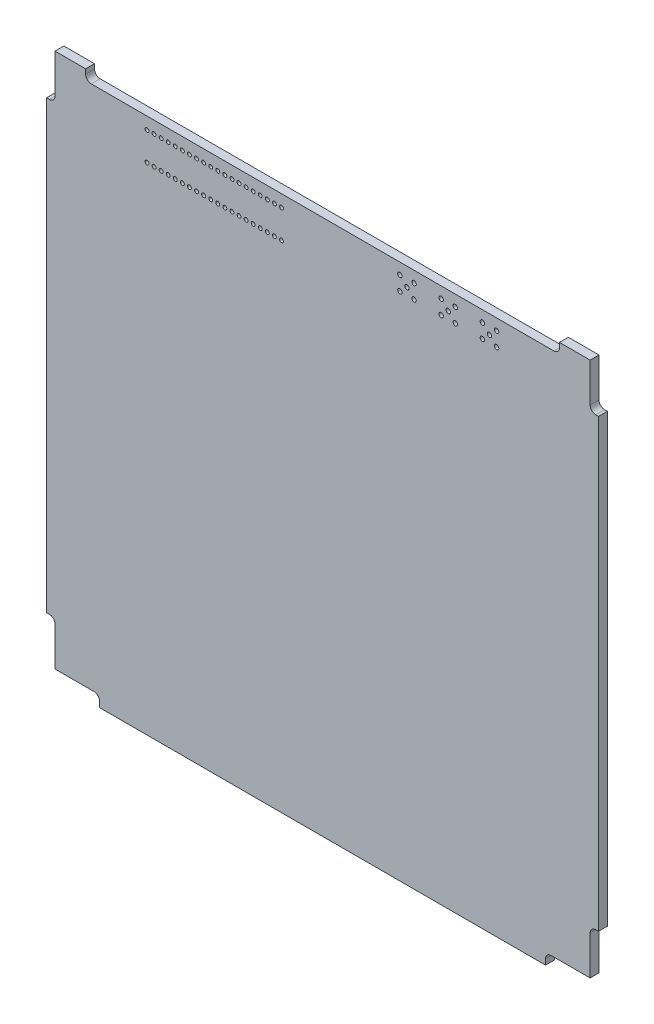
SolidWorks part; units mm, degrees
material "ABS"
ref_plane "Front Plane" through (0, 0, 0) normal (0, 0, 1) x (1, 0, 0)
ref_plane "Top Plane" through (0, 0, 0) normal (0, 1, 0) x (1, 0, 0)
ref_plane "Right Plane" through (0, 0, 0) normal (1, 0, 0) x (0, 0, -1)
sketch "Sketch1" plane through (0, 0, 0) normal (0, 0, 1) x (1, 0, 0)
  line L0 (-40, 50) -> (-40, 48)
  line L1 (-50, -50) -> (50, -50)
  line L2 (-50, -50) -> (-50, 50)
  line L3 (-50, 50) -> (50, 50)
  line L4 (50, -50) -> (50, 50)
  line L5 (-50, -50) -> (50, 50) construction
  line L6 (-50, 50) -> (50, -50) construction
  line L7 (-50, 50) -> (-40, 50)
  line L8 (-50, 50) -> (-50, 40)
  line L9 (-40, 48) -> (-48, 48)
  line L10 (-48, 48) -> (-48, 40)
  line L11 (50, 50) -> (40, 50)
  line L12 (50, 50) -> (50, 40)
  line L13 (-48, 40) -> (-50, 40)
  line L14 (50, 40) -> (48, 40)
  line L15 (-50, -50) -> (-37.8649, -50)
  line L16 (-50, -50) -> (-50, -37.8649)
  line L17 (50, 50) -> (50, 40)
  line L18 (50, 50) -> (40, 50)
  line L19 (50, -50) -> (41.5, -50)
  line L20 (50, -50) -> (50, -41.5)
  line L21 (48, 40) -> (48, 48)
  line L22 (48, 48) -> (40, 48)
  line L23 (40, 48) -> (40, 50)
  line L24 (40, -50) -> (40, -48)
  line L25 (50, -50) -> (40, -50)
  line L26 (50, -50) -> (50, -40)
  line L27 (40, -48) -> (48, -48)
  line L28 (48, -48) -> (48, -40)
  line L29 (48, -40) -> (50, -40)
  line L30 (-50, -40) -> (-48, -40)
  line L31 (-50, -50) -> (-50, -40)
  line L32 (-50, -50) -> (-40, -50)
  line L33 (-48, -40) -> (-48, -48)
  line L34 (-48, -48) -> (-40, -48)
  line L35 (-40, -48) -> (-40, -50)
  point P0 (0, 0)
  point P38 (0, 0)
  dimension "D1" = 100
  dimension "D2" = 100
  dimension "D3" = 2
  dimension "D4" = 10
  dimension "D5" = 4
extrude "Boss-Extrude1" add sketch "Sketch1" along normal blind 1.5875
sketch "Sketch2" plane through (0, 0, 1.5875) normal (0, 0, 1) x (1, 0, 0)
  line L0 (0, 50) -> (0, -50) construction
  line L1 (-40, 50) -> (40, 50) construction
  line L2 (-40, -50) -> (40, -50) construction
  line L3 (-50, -40) -> (-50, 40) construction
  line L4 (-40, 50) -> (40, 50) construction
  circle A0 centre (-31.5, 44) radius 0.35
  circle A1 centre (-30.23, 44) radius 0.35
  circle A2 centre (-28.96, 44) radius 0.35
  circle A3 centre (-27.69, 44) radius 0.35
  circle A4 centre (-26.42, 44) radius 0.35
  circle A5 centre (-25.15, 44) radius 0.35
  circle A6 centre (-23.88, 44) radius 0.35
  circle A7 centre (-22.61, 44) radius 0.35
  circle A8 centre (-21.34, 44) radius 0.35
  circle A9 centre (-20.07, 44) radius 0.35
  circle A10 centre (-18.8, 44) radius 0.35
  circle A11 centre (-17.53, 44) radius 0.35
  circle A12 centre (-16.26, 44) radius 0.35
  circle A13 centre (-14.99, 44) radius 0.35
  circle A14 centre (-13.72, 44) radius 0.35
  circle A15 centre (-12.45, 44) radius 0.35
  circle A16 centre (-11.18, 44) radius 0.35
  circle A17 centre (-9.91, 44) radius 0.35
  circle A18 centre (-8.64, 44) radius 0.35
  circle A19 centre (-7.37, 44) radius 0.35
  circle A20 centre (-30.23, 38.92) radius 0.35
  circle A21 centre (-28.96, 38.92) radius 0.35
  circle A22 centre (-27.69, 38.92) radius 0.35
  circle A23 centre (-26.42, 38.92) radius 0.35
  circle A24 centre (-25.15, 38.92) radius 0.35
  circle A25 centre (-23.88, 38.92) radius 0.35
  circle A26 centre (-22.61, 38.92) radius 0.35
  circle A27 centre (-21.34, 38.92) radius 0.35
  circle A28 centre (-20.07, 38.92) radius 0.35
  circle A29 centre (-18.8, 38.92) radius 0.35
  circle A30 centre (-17.53, 38.92) radius 0.35
  circle A31 centre (-16.26, 38.92) radius 0.35
  circle A32 centre (-14.99, 38.92) radius 0.35
  circle A33 centre (-13.72, 38.92) radius 0.35
  circle A34 centre (-12.45, 38.92) radius 0.35
  circle A35 centre (-11.18, 38.92) radius 0.35
  circle A36 centre (-9.91, 38.92) radius 0.35
  circle A37 centre (-8.64, 38.92) radius 0.35
  circle A38 centre (-7.37, 38.92) radius 0.35
  circle A39 centre (-31.5, 38.92) radius 0.35
  dimension "D1" = 0.7
  dimension "D4" = 18.5
  dimension "D5" = 6
  dimension "D2" = 5.08
  dimension "D3" = 1.27
extrude "Cut-Extrude1" cut sketch "Sketch2" against normal through all
sketch "Sketch3" plane through (0, 50, 0) normal (0, 1, 0) x (1, 0, 0)
  line L0 (-40, 0) -> (40, 0) construction
  line L1 (10.7, 0) -> (19.7, 0)
  line L2 (10.7, 0) -> (10.7, -1.5875)
  line L3 (10.7, -1.5875) -> (19.7, -1.5875)
  line L4 (-40, -1.5875) -> (-40, 0) construction
  line L5 (-40, -1.5875) -> (40, -1.5875) construction
  line L6 (15.2, 0) -> (15.2, -1.5875) construction
  line L7 (12, 0) -> (12, -1.5875) construction
  line L8 (18.4, 0) -> (18.4, -1.5875) construction
  line L9 (-40, -1.5875) -> (40, -1.5875) construction
  line L12 (19.7, 0) -> (34.5, 0)
  line L14 (19.7, -1.5875) -> (34.5, -1.5875)
  line L15 (34.5, 0) -> (34.5, -1.5875)
  dimension "D1" = 9
  dimension "D2" = 6.4
  dimension "D3" = 3.2
  dimension "D5" = 14.8
  dimension "D6" = 50.7
extrude "Cut-Extrude2" cut sketch "Sketch3" against normal blind 3.8375
fillet "Fillet2" radius 1 2 edges at (10.7, 46.1625, 0.7938) (34.5, 46.1625, 0.7937)
sketch "Sketch5" plane through (0, 0, 0) normal (0, 0, -1) x (-1, 0, 0)
  line L0 (40, -50) -> (-40, -50) construction
  line L1 (-49.5, 50) -> (49.5, 50)
  line L2 (-49.5, 50) -> (-49.5, -50)
  line L3 (-49.5, -50) -> (49.5, -50)
  line L4 (49.5, 50) -> (49.5, -50)
  line L5 (40, 50) -> (-10.7, 50) construction
  line L6 (50, -40) -> (50, 40) construction
  dimension "D1" = 99
  dimension "D2" = 0.5
extrude "Cut-Extrude3" cut sketch "Sketch5" against normal through all flip side to cut
sketch "Sketch6" plane through (0, 0, 1.5875) normal (0, 0, 1) x (1, 0, 0)
  line L0 (11.7, 46.1625) -> (33.5, 46.1625) construction
  line L1 (28.67, 41.6225) -> (31.21, 41.6225) construction
  line L2 (28.67, 41.6225) -> (28.67, 44.1625) construction
  line L3 (28.67, 44.1625) -> (31.21, 44.1625) construction
  line L4 (31.21, 41.6225) -> (31.21, 44.1625) construction
  line L5 (28.67, 41.6225) -> (31.21, 44.1625) construction
  line L6 (28.67, 44.1625) -> (31.21, 41.6225) construction
  line L7 (34.5, 47.1625) -> (34.5, 50) construction
  line L8 (21.27, 41.6225) -> (23.81, 41.6225) construction
  line L9 (21.27, 41.6225) -> (21.27, 44.1625) construction
  line L10 (21.27, 44.1625) -> (23.81, 44.1625) construction
  line L11 (23.81, 41.6225) -> (23.81, 44.1625) construction
  line L12 (21.27, 41.6225) -> (23.81, 44.1625) construction
  line L13 (21.27, 44.1625) -> (23.81, 41.6225) construction
  line L14 (13.87, 41.6225) -> (16.41, 41.6225) construction
  line L17 (13.87, 41.6225) -> (13.87, 44.1625) construction
  line L18 (13.87, 44.1625) -> (16.41, 44.1625) construction
  line L19 (16.41, 41.6225) -> (16.41, 44.1625) construction
  line L20 (13.87, 41.6225) -> (16.41, 44.1625) construction
  line L21 (13.87, 44.1625) -> (16.41, 41.6225) construction
  circle A0 centre (29.94, 42.8925) radius 0.4
  circle A1 centre (28.67, 44.1625) radius 0.4
  circle A2 centre (31.21, 44.1625) radius 0.4
  circle A3 centre (31.21, 41.6225) radius 0.4
  circle A4 centre (28.67, 41.6225) radius 0.4
  circle A5 centre (22.54, 42.8925) radius 0.4
  circle A6 centre (21.27, 44.1625) radius 0.4
  circle A7 centre (23.81, 44.1625) radius 0.4
  circle A8 centre (23.81, 41.6225) radius 0.4
  circle A9 centre (21.27, 41.6225) radius 0.4
  circle A10 centre (15.14, 42.8925) radius 0.4
  circle A11 centre (13.87, 44.1625) radius 0.4
  circle A12 centre (16.41, 44.1625) radius 0.4
  circle A13 centre (16.41, 41.6225) radius 0.4
  circle A14 centre (13.87, 41.6225) radius 0.4
  point P23 (27.2, 39.7784)
  point P32 (19.8, 39.7784)
  dimension "D1" = 2.54
  dimension "D2" = 0.8
  dimension "D3" = 2.54
  dimension "D4" = 3.27
  dimension "D5" = 4.56
  dimension "D6" = 7.4
  dimension "D8" = 2
  dimension "D7" = 3
sketch "Sketch7" plane through (0, 0, 1.5875) normal (0, 0, 1) x (1, 0, 0)
  line L0 (-40, 50) -> (-36.5, 50)
  line L1 (-40, 50) -> (10.7, 50) construction
  line L2 (-36.5, 50) -> (-36.5, 48)
  line L3 (-36.5, 48) -> (-41.5, 48)
  line L4 (-40, 48) -> (-48, 48) construction
  line L5 (-41.5, 48) -> (-41.5, 41.5)
  line L6 (-41.5, 41.5) -> (-42, 41.5)
  line L7 (-47, 36.5) -> (-47, -36.5)
  line L8 (-40, 50) -> (-49.5, 50)
  line L9 (-49.5, 50) -> (-49.5, -50)
  line L10 (-49.5, -40) -> (-49.5, 40) construction
  line L11 (49.5, 0) -> (-49.5, 0) construction
  line L12 (-40, -50) -> (-49.5, -50)
  line L13 (-41.5, -41.5) -> (-42, -41.5)
  line L14 (-41.5, -48) -> (-41.5, -41.5)
  line L15 (-36.5, -48) -> (-41.5, -48)
  line L16 (-36.5, -50) -> (-36.5, -48)
  line L17 (-40, -50) -> (-36.5, -50)
  line L18 (0, 0) -> (0, -14.0383) construction
  line L19 (40, -50) -> (36.5, -50)
  line L20 (36.5, -50) -> (36.5, -48)
  line L21 (36.5, -48) -> (41.5, -48)
  line L22 (41.5, -48) -> (41.5, -41.5)
  line L23 (41.5, -41.5) -> (42, -41.5)
  line L24 (40, -50) -> (49.5, -50)
  line L25 (49.5, 50) -> (49.5, -50)
  line L26 (40, 50) -> (49.5, 50)
  line L27 (47, 36.5) -> (47, -36.5)
  line L28 (41.5, 41.5) -> (42, 41.5)
  line L29 (41.5, 48) -> (41.5, 41.5)
  line L30 (36.5, 48) -> (41.5, 48)
  line L31 (36.5, 50) -> (36.5, 48)
  line L32 (40, 50) -> (36.5, 50)
  arc A0 (-42, 41.5) -> (-47, 36.5) centre (-42, 36.5) ccw
  arc A1 (-42, -41.5) -> (-47, -36.5) centre (-42, -36.5) cw
  arc A2 (42, -41.5) -> (47, -36.5) centre (42, -36.5) ccw
  arc A3 (42, 41.5) -> (47, 36.5) centre (42, 36.5) cw
  point P25 (-47, 0)
  point P32 (0, 0)
  point P50 (47, 0)
  dimension "D1" = 5
  dimension "D2" = 13
  dimension "D3" = 8
  dimension "D4" = 8.5
  dimension "D5" = 2.5
  dimension "D6" = 5
sketch "Sketch8" plane through (0, 50, 0) normal (0, 1, 0) x (1, 0, 0)
  line L0 (34.5, -1.5875) -> (40, -1.5875) construction
  line L1 (-42.5, 0) -> (42.5, 0)
  line L2 (-42.5, 0) -> (-42.5, -1.5875)
  line L3 (-42.5, -1.5875) -> (42.5, -1.5875)
  line L4 (42.5, 0) -> (42.5, -1.5875)
  line L5 (-42.5, 0) -> (42.5, -1.5875) construction
  line L6 (-42.5, -1.5875) -> (42.5, 0) construction
  line L8 (-40, -1.5875) -> (-40, 0) construction
  point P0 (0, -0.7937)
  dimension "D1" = 85
  dimension "D2" = 1.5875
  dimension "D3" = 2.5
extrude "Cut-Extrude4" cut sketch "Sketch8" against normal blind 3.8375
fillet "Fillet1" radius 1 8 edges at (-48, -40, 0.7937) (-40, -48, 0.7937) (40, -48, 0.7937) (48, -40, 0.7937) (48, 40, 0.7937) (-48, 40, 0.7937) (42.5, 46.1625, 0.7937) (-42.5, 46.1625, 0.7937)
sketch "Sketch10" plane through (0, 0, 1.5875) normal (0, 0, 1) x (1, 0, 0)
  line L1 (-41.25, 48) -> (41.25, 48)
  line L2 (-41.25, 48) -> (-41.25, 46.4125)
  line L3 (-41.25, 46.4125) -> (41.25, 46.4125)
  line L4 (41.25, 48) -> (41.25, 46.4125)
  line L5 (-41.25, 48) -> (41.25, 46.4125) construction
  line L6 (-41.25, 46.4125) -> (41.25, 48) construction
  line L7 (-36.5, 48) -> (-41.5, 48) construction
  line L9 (41.5, 48) -> (41.5, 41.5) construction
  point P0 (0, 47.2062)
  dimension "D1" = 82.5
  dimension "D2" = 1.5875
  dimension "D3" = 0.25
extrude "Cut-Extrude5" cut sketch "Sketch6" against normal through all
